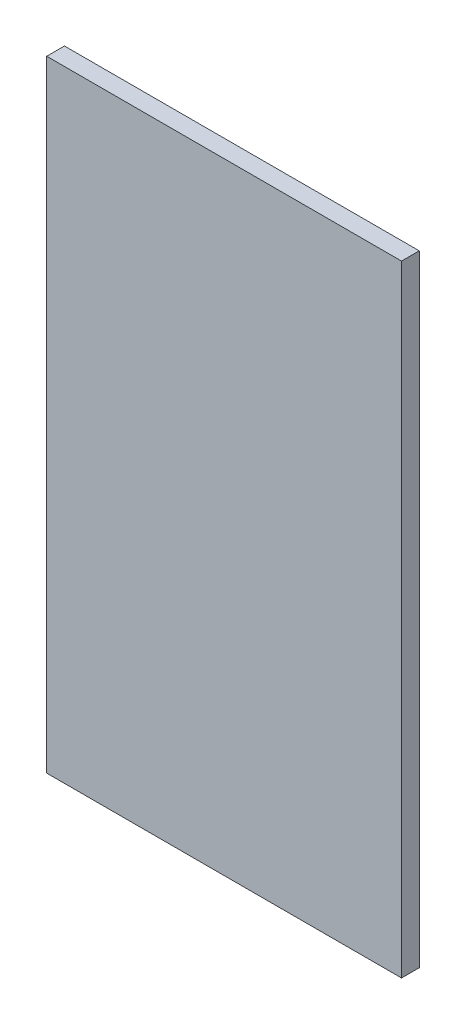
SolidWorks part; units mm, degrees
ref_plane "Front Plane" through (0, 0, 0) normal (0, 0, 1) x (1, 0, 0)
ref_plane "Top Plane" through (0, 0, 0) normal (0, 1, 0) x (1, 0, 0)
ref_plane "Right Plane" through (0, 0, 0) normal (1, 0, 0) x (0, 0, -1)
sketch "Sketch1" plane through (0, 0, 0) normal (0, 0, 1) x (1, 0, 0)
  line L1 (0, 0) -> (400, 0)
  line L2 (0, 0) -> (0, 700)
  line L3 (0, 700) -> (400, 700)
  line L4 (400, 0) -> (400, 700)
  dimension "D1" = 700
  dimension "D2" = 400
extrude "Boss-Extrude1" add sketch "Sketch1" along normal blind 20
